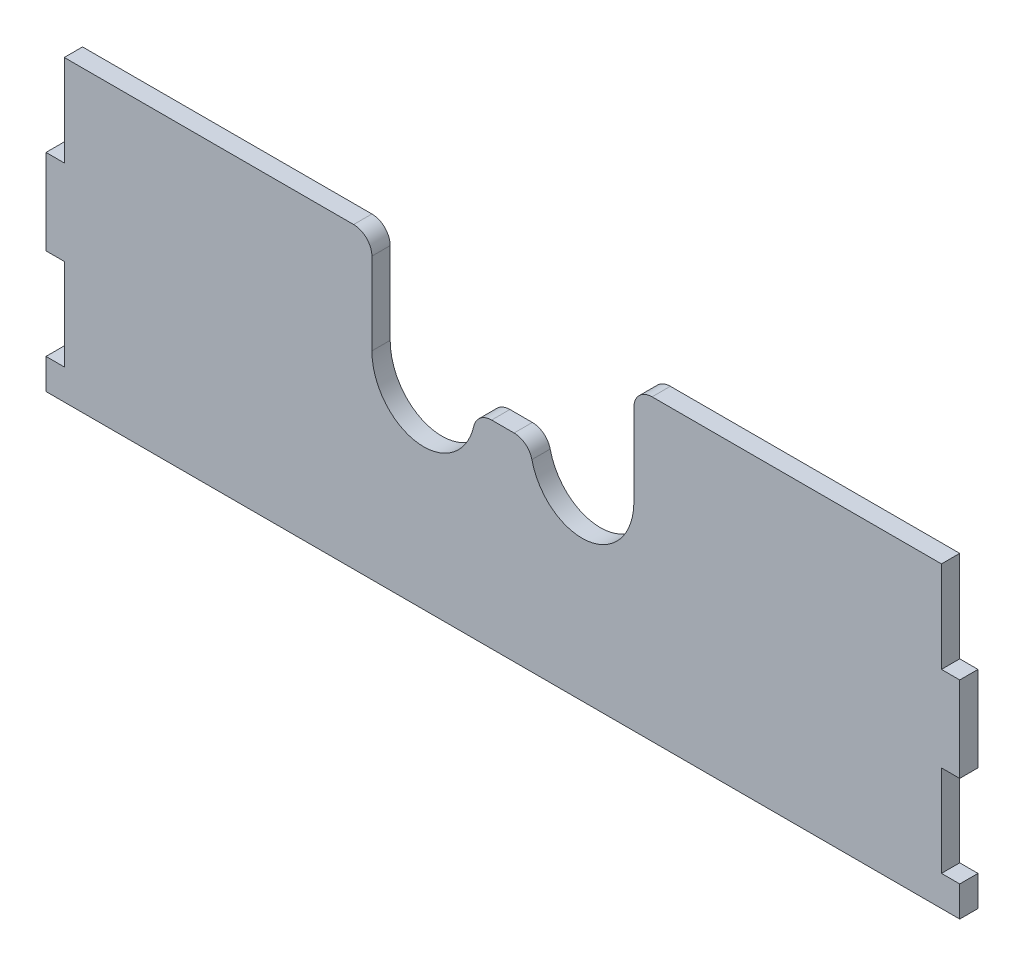
SolidWorks part; units mm, degrees
ref_plane "Alzado" through (0, 0, 0) normal (0, 0, 1) x (1, 0, 0)
ref_plane "Planta" through (0, 0, 0) normal (0, 1, 0) x (1, 0, 0)
ref_plane "Vista lateral" through (0, 0, 0) normal (1, 0, 0) x (0, 0, -1)
sketch "Croquis1" plane through (0, 0, 0) normal (0, 0, 1) x (1, 0, 0)
  line L0 (0, 0) -> (0, 19.9961) construction
  line L1 (-75, -25) -> (75, -25)
  line L2 (-75, -25) -> (-75, 25)
  line L3 (-75, 25) -> (75, 25)
  line L4 (75, -25) -> (75, 25)
  line L5 (-75, -25) -> (75, 25) construction
  line L6 (-75, 25) -> (75, -25) construction
  line L7 (-75, -19) -> (-72, -19)
  line L8 (-75, -19) -> (-75, -4)
  line L9 (-75, -4) -> (-72, -4)
  line L10 (-72, -19) -> (-72, -4)
  line L11 (-75, 10) -> (-72, 10)
  line L12 (-75, 10) -> (-75, 25)
  line L13 (-75, 25) -> (-72, 25)
  line L14 (-72, 10) -> (-72, 25)
  line L15 (72, 10) -> (72, 25)
  line L16 (75, 25) -> (72, 25)
  line L17 (75, 10) -> (75, 25)
  line L18 (75, 10) -> (72, 10)
  line L19 (72, -19) -> (72, -4)
  line L20 (75, -4) -> (72, -4)
  line L21 (75, -19) -> (75, -4)
  line L22 (75, -19) -> (72, -19)
  point P0 (0, 0)
  dimension "D1" = 150
  dimension "D2" = 50
  dimension "D3" = 3
  dimension "D4" = 15
  dimension "D5" = 15
  dimension "D6" = 14
extrude "Saliente-Extruir1" add sketch "Croquis1" along normal blind 3 contours L4 L22 L19 L20 L18 L15 L16 L3 L2 L13 L14 L11 L9 L10 L7 L1
ref_plane "Plano1" through (0, 4.4652, -9.5756) normal (0, -0.4226, 0.9063) x (1, 0, 0)
sketch "Croquis2" plane through (0, 2.3423, -10.5655) normal (0, -0.4226, 0.9063) x (1, 0, 0)
  line L0 (-13, 11.3423) -> (13, 11.3423) construction
  circle A0 centre (-13, 11.3423) radius 8.5
  circle A1 centre (13, 11.3423) radius 8.5
  point P3 (0, 11.3423)
  dimension "D1" = 17
  dimension "D2" = 26
  dimension "D3" = 9
extrude "Cortar-Extruir1" cut sketch "Croquis2" along normal through all
sketch "Croquis3" plane through (0, 0, 0) normal (0, 0, 1) x (1, 0, 0)
  ellipse E0 centre (13, 8.5315) end of major axis (13, 17.9102) minor radius 8.5 construction
  ellipse E1 centre (13, 9.9304) end of major axis (13, 19.3091) minor radius 8.5 construction
  ellipse E2 centre (-13, 8.5315) end of major axis (-13, -0.8472) minor radius 8.5 construction
  ellipse E3 centre (-13, 9.9304) end of major axis (-13, 19.3091) minor radius 8.5 construction
  ellipse E4 centre (13, 8.5315) end of major axis (13, 17.9102) minor radius 8.5
  ellipse E5 centre (13, 9.9304) end of major axis (13, 19.3091) minor radius 8.5
  ellipse E6 centre (-13, 8.5315) end of major axis (-13, 17.9102) minor radius 8.5
  ellipse E7 centre (-13, 9.9304) end of major axis (-13, 19.3091) minor radius 8.5
extrude "Cortar-Extruir2" cut sketch "Croquis3" along normal blind 3 contours E6 E7 | E7 E6 | E5 E4 | E4 E5 | E4 E5 | E6 E7
sketch "Croquis4" plane through (0, 0, 0) normal (0, 0, 1) x (1, 0, 0)
  line L0 (-72, 25) -> (72, 25) construction
  line L1 (-21.5, 25) -> (21.5, 25)
  line L2 (-21.5, 25) -> (-21.5, 8.5315)
  line L3 (-21.5, 8.5315) -> (21.5, 8.5315)
  line L4 (21.5, 25) -> (21.5, 8.5315)
extrude "Cortar-Extruir3" cut sketch "Croquis4" along normal through all
fillet "Redondeo1" radius 3 4 edges at (4.5, 8.5315, 1.5) (-4.5, 8.5315, 1.5) (21.5, 25, 1.5) (-21.5, 25, 1.5)
sketch "Croquis5" plane through (0, 0, 0) normal (0, 0, 1) x (1, 0, 0)
  line L0 (75, -25) -> (75, -19) construction
  line L1 (-75, -25) -> (75, -25)
  line L2 (-75, -25) -> (-75, -24)
  line L3 (-75, -24) -> (75, -24)
  line L4 (75, -25) -> (75, -24)
  dimension "D1" = 1
extrude "Cortar-Extruir4" cut sketch "Croquis5" along normal through all
